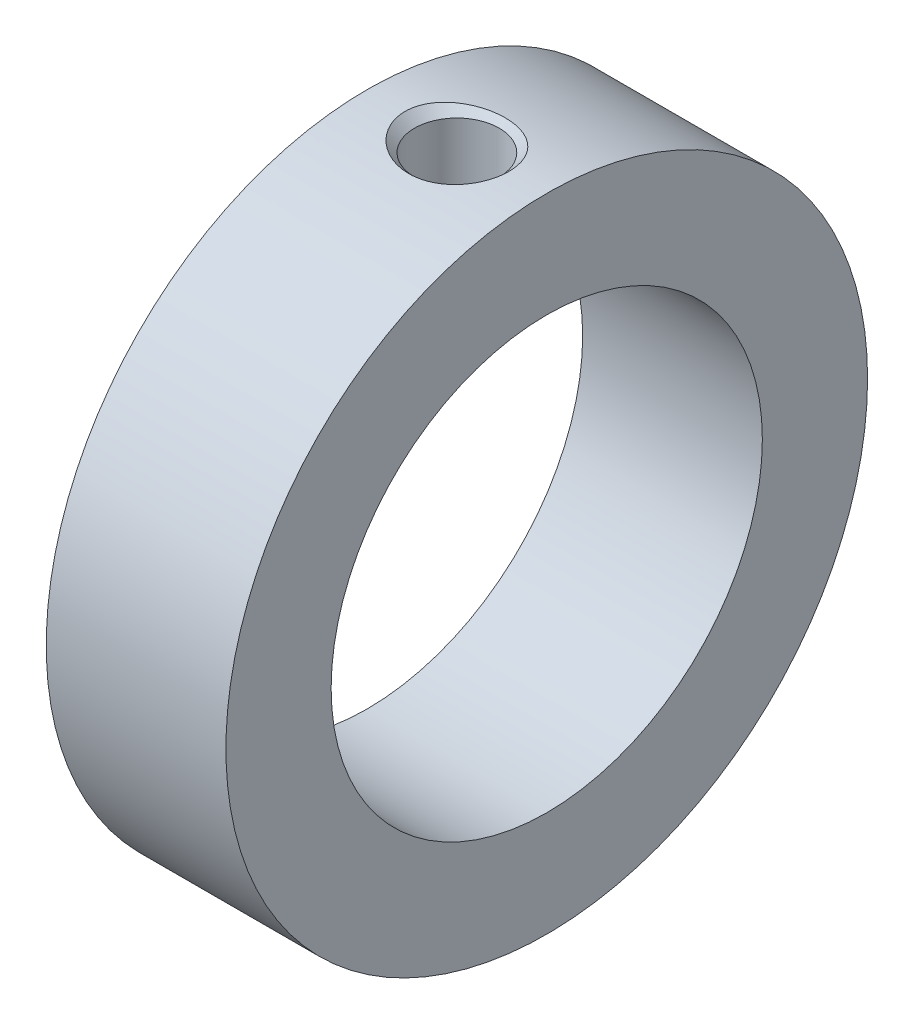
SolidWorks part; units mm, degrees
ref_plane "Front Plane" through (0, 0, 0) normal (0, 0, 1) x (1, 0, 0)
ref_plane "Top Plane" through (0, 0, 0) normal (0, 1, 0) x (1, 0, 0)
ref_plane "Right Plane" through (0, 0, 0) normal (1, 0, 0) x (0, 0, -1)
sketch "Sketch1" plane through (0, 0, 0) normal (1, 0, 0) x (0, 0, -1)
  circle A0 centre (0, 0) radius 12.5
  circle A1 centre (0, 0) radius 8.4
  dimension "D1" = 25
  dimension "D2" = 16.8
extrude "Boss-Extrude1" add sketch "Sketch1" along normal blind 7
hole_wizard "M4 Tapped Hole1" positions "3DSketch1" profile "Sketch2" tap size "M4" standard "ISO"
sketch3d "3DSketch1"
  line L0 (0, 12.5, 0) -> (7, 12.5, 0) construction
  circle A0 centre (0, 0, 0) radius 12.5 construction
  circle A1 centre (7, 0, 0) radius 12.5 construction
  point P0 (3.5, 12.5, 0)
  point P7 (12.5, 0, 0)
  point P10 (19.5, 0, 0)
sketch "Sketch2" plane through (3.5, 12.5, 0) normal (1, 0, 0) x (0, 0, 1)
  line L0 (0, 0) -> (0, 12.4914)
  line L1 (0, 12.4914) -> (1.65, 11.5)
  line L2 (1.65, 11.5) -> (1.65, 0.375)
  line L3 (1.65, 0.375) -> (2.025, 0)
  line L5 (2.025, 0) -> (0, 0)
  line L6 (-1.65, 0.375) -> (-2.025, 0) construction
  line L10 (0, 12.4914) -> (-1.65, 11.5) construction
  line L11 (0, -6.35) -> (0, 107.95) construction
  dimension "Tap Drill Dia." = 3.3
  dimension "Tap Drill Depth" = 11.5
  dimension "Near C'Sink Dia." = 4.05
  dimension "Near C'Sink Angle" = 90
  dimension "Drill Angle" = 118
cosmetic thread "Hole Thread1" parameters "D1"=4.672, "D2"=4
move or copy body "Body-Move/Copy1" [suppressed] bodies to move or copy 103
